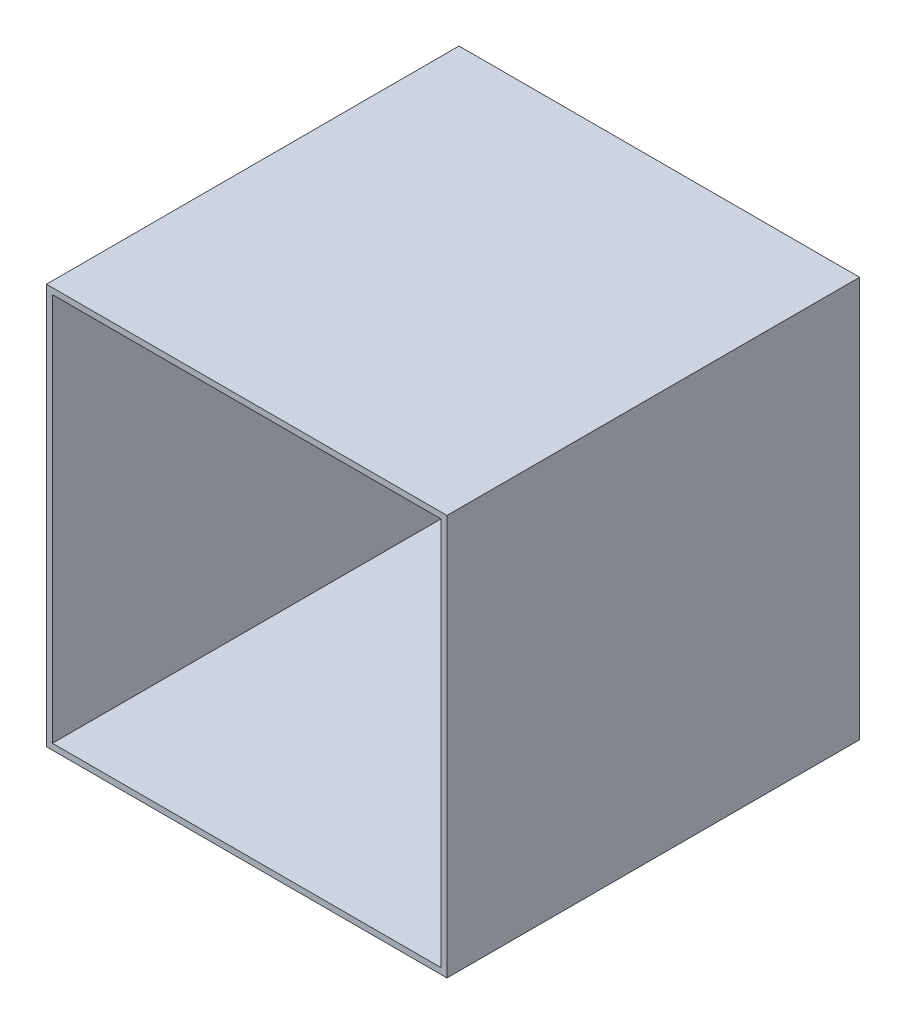
SolidWorks part; units mm, degrees
ref_plane "Front Plane" through (0, 0, 0) normal (1, 0, 0) x (0, 1, 0)
ref_plane "Top Plane" through (0, 0, 0) normal (0, 0, 1) x (0, 1, 0)
ref_plane "Right Plane" through (0, 0, 0) normal (0, 1, 0) x (-1, 0, 0)
sketch "Sketch1" plane through (0, 0, 0) normal (0, 0, 1) x (0, 1, 0)
  line L5 (-50, 50) -> (50, 50)
  line L6 (-50, 50) -> (-50, -50)
  line L7 (-50, -50) -> (50, -50)
  line L8 (50, 50) -> (50, -50)
  line L9 (-50, 50) -> (50, -50) construction
  line L10 (-50, -50) -> (50, 50) construction
  point P0 (0, 0)
  dimension "D1" = 100
  dimension "D2" = 100
extrude "Boss-Extrude1" add sketch "Sketch1" along normal blind 3
sketch "Sketch4" plane through (0, 0, 3) normal (0, 0, 1) x (1, 0, 0)
  line L1 (-50, 50) -> (50, 50)
  line L2 (-50, 50) -> (-50, -50)
  line L3 (-50, -50) -> (50, -50)
  line L4 (50, 50) -> (50, -50)
  line L5 (-50, 50) -> (50, -50) construction
  line L6 (-50, -50) -> (50, 50) construction
  point P0 (0, 0)
extrude "Boss-Extrude2" add sketch "Sketch4" along normal blind 100
sketch "Sketch5" plane through (0, 0, 103) normal (0, 0, 1) x (1, 0, 0)
  line L1 (-48.5, 48.5) -> (48.5, 48.5)
  line L2 (-48.5, 48.5) -> (-48.5, -48.5)
  line L3 (-48.5, -48.5) -> (48.5, -48.5)
  line L4 (48.5, 48.5) -> (48.5, -48.5)
  line L5 (-48.5, 48.5) -> (48.5, -48.5) construction
  line L6 (-48.5, -48.5) -> (48.5, 48.5) construction
  point P0 (0, 0)
  dimension "D1" = 97
  dimension "D2" = 97
extrude "Cut-Extrude1" cut sketch "Sketch5" against normal blind 100
sketch "Sketch6" plane through (0, -50, 0) normal (0, -1, 0) x (1, 0, 0)
  circle A0 centre (-45.6938, 4.5712) radius 1
  circle A1 centre (-38.4384, 4.5712) radius 1
  circle A2 centre (-29.7936, 4.5712) radius 1
  dimension "D1" = 2
  dimension "D2" = 2
  dimension "D3" = 2
extrude "Cut-Extrude2" cut sketch "Sketch6" against normal blind 3
sketch "Sketch7" plane through (0, -50, 0) normal (0, -1, 0) x (1, 0, 0)
  line L0 (-12.6584, 4.3) -> (6.1416, 4.3)
  line L2 (-12.6584, 4.3) -> (-12.6584, 18)
  line L3 (-12.6584, 18) -> (6.1416, 18)
  line L5 (-50, 103) -> (50, 103) construction
  line L7 (6.1416, 4.3) -> (6.1416, 18)
  point P0 (0, 0)
  dimension "D1" = 18.8
  dimension "D2" = 13.7
  dimension "D3" = 85
extrude "Cut-Extrude3" cut sketch "Sketch7" against normal blind 3
sketch "Sketch8" plane through (0, -50, 0) normal (0, -1, 0) x (1, 0, 0)
  line L0 (19.7958, 7.72) -> (26.8558, 7.72) construction
  line L1 (19.7958, 9) -> (26.8558, 9)
  line L2 (19.7958, 6.44) -> (26.8558, 6.44)
  line L3 (-50, 103) -> (50, 103) construction
  arc A0 (19.7958, 9) -> (19.7958, 6.44) centre (19.7958, 7.72) ccw
  arc A1 (26.8558, 6.44) -> (26.8558, 9) centre (26.8558, 7.72) ccw
  point P2 (23.3258, 7.72)
  point P7 (28.1358, 7.72)
  dimension "D1" = 8.34
  dimension "D2" = 2.56
  dimension "D3" = 94
extrude "Cut-Extrude4" cut sketch "Sketch8" against normal blind 3
